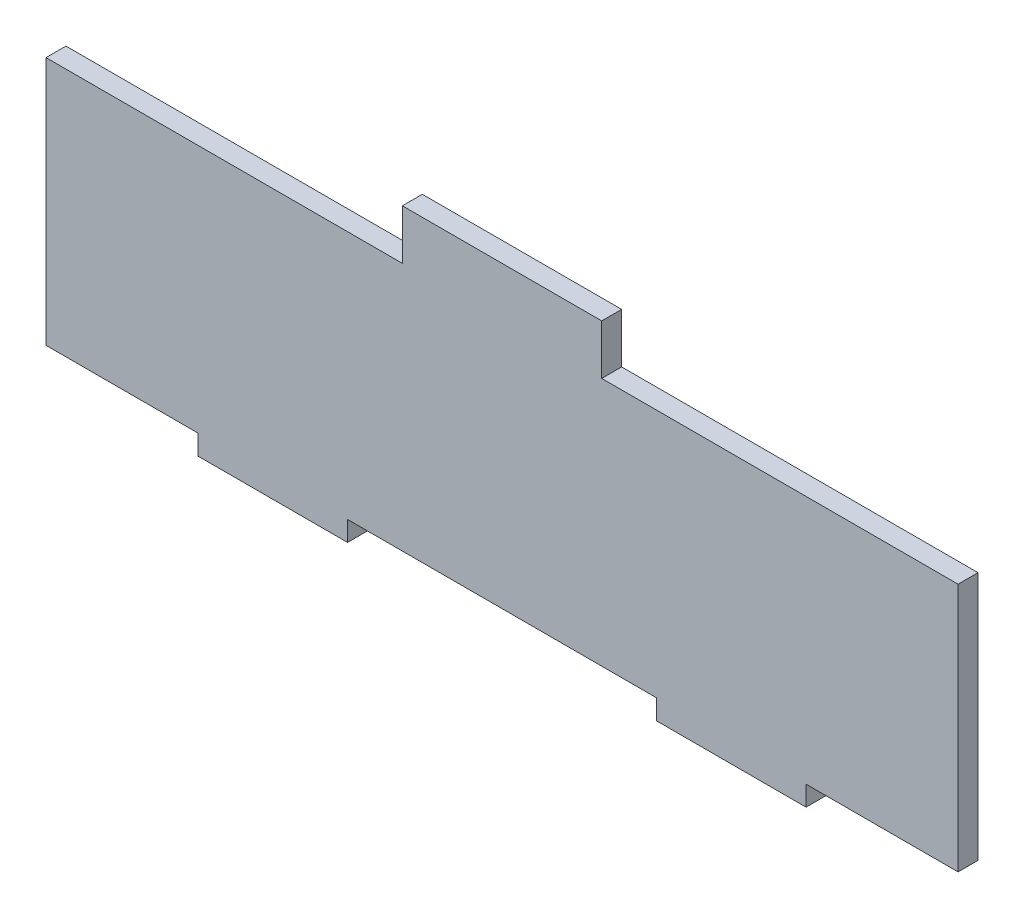
SolidWorks part; units mm, degrees
material "Aleación 6061"
ref_plane "Alzado" through (0, 0, 0) normal (0, 0, 1) x (1, 0, 0)
ref_plane "Planta" through (0, 0, 0) normal (0, 1, 0) x (1, 0, 0)
ref_plane "Vista lateral" through (0, 0, 0) normal (1, 0, 0) x (0, 0, -1)
sketch "Croquis1" plane through (0, 0, 0) normal (0, 0, 1) x (1, 0, 0)
  line L0 (-61, -25) -> (-61, -29)
  line L1 (-91.5, -25) -> (-61, -25)
  line L2 (-91.5, -25) -> (-91.5, 25)
  line L3 (-91.5, 25) -> (-20, 25)
  line L4 (91.5, -25) -> (91.5, 25)
  line L5 (-91.5, -25) -> (91.5, 25) construction
  line L6 (-91.5, 25) -> (91.5, -25) construction
  line L7 (-61, -29) -> (-31, -29)
  line L8 (-31, -29) -> (-31, -25)
  line L9 (-31, -25) -> (31, -25)
  line L10 (31, -25) -> (31, -29)
  line L11 (31, -29) -> (61, -29)
  line L12 (61, -29) -> (61, -25)
  line L13 (61, -25) -> (91.5, -25)
  line L14 (-20, 25) -> (-20, 35)
  line L15 (-20, 35) -> (20, 35)
  line L16 (20, 35) -> (20, 25)
  line L17 (20, 25) -> (91.5, 25)
  point P0 (0, 0)
  point P6 (-46, -25)
  point P9 (-46, -29)
  point P12 (46, -25)
  point P15 (46, -29)
  point P20 (0, -25)
  point P23 (0, 35)
  dimension "D1" = 183
  dimension "D2" = 50
  dimension "D3" = 45.5
  dimension "D4" = 30
  dimension "D5" = 4
  dimension "D6" = 45.5
  dimension "D7" = 40
  dimension "D8" = 10
extrude "Saliente-Extruir1" add sketch "Croquis1" along normal blind 4
